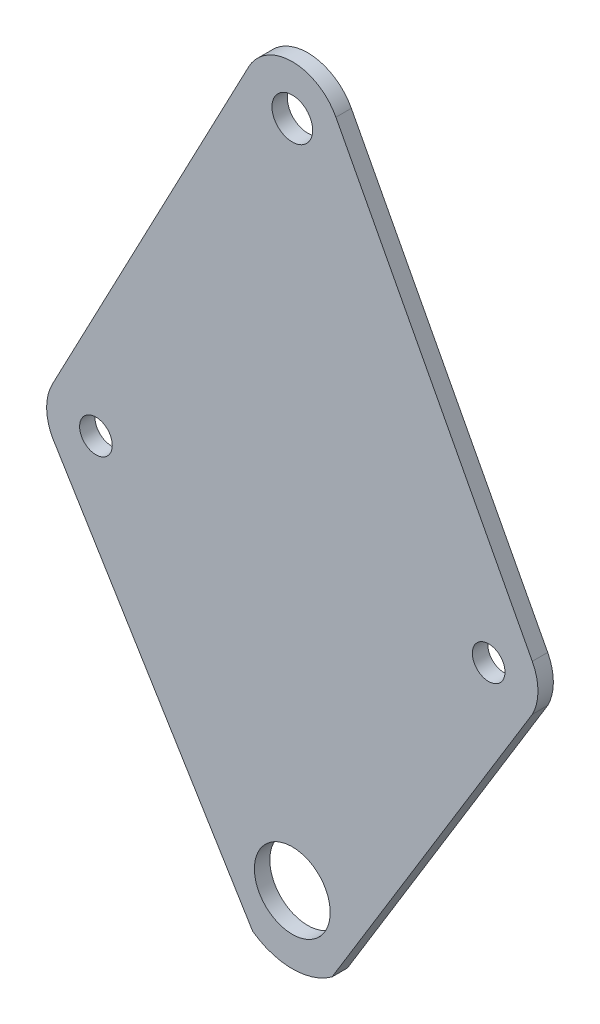
SolidWorks part; units mm, degrees
material "Custom Plastic"
ref_plane "X-Y Datum" through (0, 0, 0) normal (0, 0, 1) x (1, 0, 0)
ref_plane "X-Z Datum" through (0, 0, 0) normal (0, 1, 0) x (1, 0, 0)
ref_plane "Y-Z Datum" through (0, 0, 0) normal (1, 0, 0) x (0, 0, -1)
sketch "Rocker Ref Sketch" plane through (0, 0, 0) normal (0, 0, 1) x (1, 0, 0)
  line L0 (0, 0) -> (0, 137.7747) construction
  line L1 (0, 137.7747) -> (40.4627, 60.9059) construction
  line L2 (40.4627, 60.9059) -> (0, 0) construction
  line L3 (-13.97, 0) -> (-10.16, 137.7747)
  line L4 (8.9905, 142.5072) -> (49.4532, 65.6383)
  line L5 (49.4532, 56.1734) -> (8.1778, -11.3263)
  circle A0 centre (0, 0) radius 7.8105
  circle A1 centre (40.4627, 60.9059) radius 3.3655
  circle A2 centre (0, 137.7747) radius 4.191
  arc A3 (-10.16, 137.7747) -> (8.9905, 142.5072) centre (0, 137.7747) cw
  arc A4 (49.4532, 65.6383) -> (49.4532, 56.1734) centre (40.4627, 60.9059) cw
  arc A5 (8.1778, -11.3263) -> (-13.97, 0) centre (0, 0) cw
  arc A6 (-10.16, 137.7747) -> (-13.97, 0) centre (-120.7988, 71.8942) cw
  circle A7 centre (0, 0) radius 11.5718
  point P16 (50.6227, 60.9059)
  dimension "D4" = 15.621
  dimension "D5" = 6.731
  dimension "D6" = 8.382
  dimension "D7" = 13.97
  dimension "D8" = 10.16
  dimension "D9" = 10.16
  dimension "D1" = 137.7747
  dimension "D2" = 86.868
  dimension "D3" = 73.1215
  dimension "D11" = 125.83
sketch "Sketch4" plane through (0, 0, 0) normal (0, 0, 1) x (1, 0, 0)
  line L0 (8.9905, 142.5072) -> (49.4532, 65.6383) construction
  line L1 (49.4532, 65.6383) -> (8.9905, 142.5072)
  line L2 (-10.16, 137.7747) -> (-13.97, 0)
  line L3 (8.1778, -11.3263) -> (49.4532, 56.1734)
  line L6 (40.4627, 60.9059) -> (-12.2857, 60.9059) construction
  line L7 (0, 137.7747) -> (0, 0) construction
  line L8 (0, 0) -> (0, 137.7747) construction
  line L9 (10.16, 137.7747) -> (13.97, 0)
  line L10 (-49.4532, 65.6383) -> (-8.9905, 142.5072)
  line L11 (-8.1778, -11.3263) -> (-49.4532, 56.1734)
  circle A1 centre (40.4627, 60.9059) radius 3.3655
  arc A2 (49.4532, 56.1734) -> (49.4532, 65.6383) centre (40.4627, 60.9059) ccw
  circle A3 centre (0, 137.7747) radius 4.191
  circle A5 centre (0, 0) radius 7.8105
  arc A6 (8.9905, 142.5072) -> (-10.16, 137.7747) centre (0, 137.7747) ccw
  arc A7 (8.9905, 142.5072) -> (-10.16, 137.7747) centre (0, 137.7747) ccw construction
  arc A8 (-13.97, 0) -> (8.1778, -11.3263) centre (0, 0) ccw
  arc A9 (-13.97, 0) -> (8.1778, -11.3263) centre (0, 0) ccw construction
  circle A10 centre (-40.4627, 60.9059) radius 3.3655
  arc A11 (13.97, 0) -> (-8.1778, -11.3263) centre (0, 0) cw
  arc A12 (-8.9905, 142.5072) -> (10.16, 137.7747) centre (0, 137.7747) cw
  arc A13 (-49.4532, 56.1734) -> (-49.4532, 65.6383) centre (-40.4627, 60.9059) cw
  dimension "D1" = 6.731
  dimension "D2" = 8.382
  dimension "D3" = 15.621
  dimension "D4" = 79.1193
  dimension "D5" = 137.7747
extrude "Boss-Extrude4" add sketch "Sketch4" along normal blind 3.175 contours A13 L11 A8 L2 A6 L10 A10 | L1 A12 L9 A11 L3 A2 A1 | A12 A6 L2 A8 L11 L3 A11 L9 A3 A5
